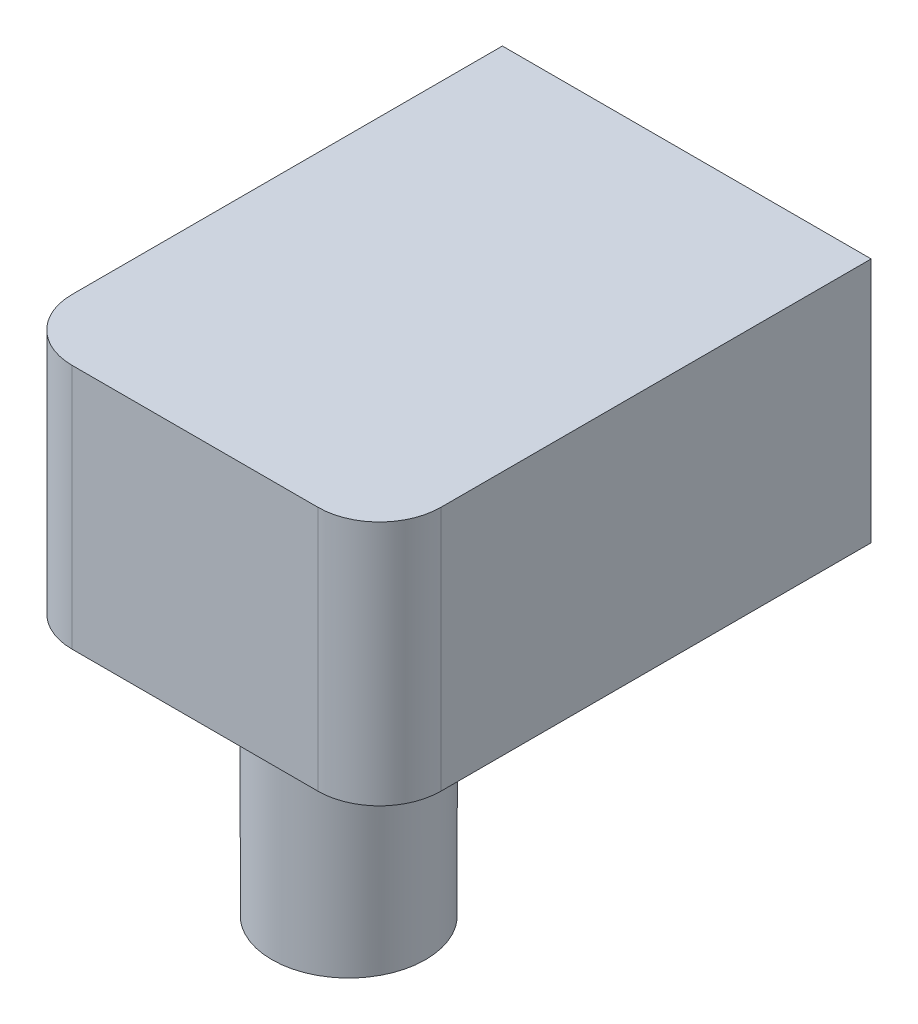
SolidWorks part; units mm, degrees
ref_plane "Alzado" through (0, 0, 0) normal (0, 0, 1) x (1, 0, 0)
ref_plane "Planta" through (0, 0, 0) normal (0, 1, 0) x (1, 0, 0)
ref_plane "Vista lateral" through (0, 0, 0) normal (1, 0, 0) x (0, 0, -1)
sketch "Croquis1" plane through (0, 0, 0) normal (0, 0, 1) x (1, 0, 0)
  line L1 (-30, -20) -> (30, -20)
  line L2 (-30, -20) -> (-30, 20)
  line L3 (-30, 20) -> (30, 20)
  line L4 (30, -20) -> (30, 20)
  line L5 (-30, -20) -> (30, 20) construction
  line L6 (-30, 20) -> (30, -20) construction
  point P0 (0, 0)
  dimension "D1" = 60
  dimension "D2" = 40
extrude "Saliente-Extruir1" add sketch "Croquis1" along normal blind 80
fillet "Redondeo1" radius 10 2 edges at (30, 0, 80) (-30, 0, 80)
sketch "Croquis2" plane through (0, -20, 0) normal (0, -1, 0) x (1, 0, 0)
  line L0 (0, 80) -> (0, 55) construction
  line L1 (-20, 80) -> (20, 80) construction
  circle A0 centre (0, 55) radius 12.5
  dimension "D2" = 25
  dimension "D1" = 25
extrude "Saliente-Extruir2" add sketch "Croquis2" along normal blind 40
